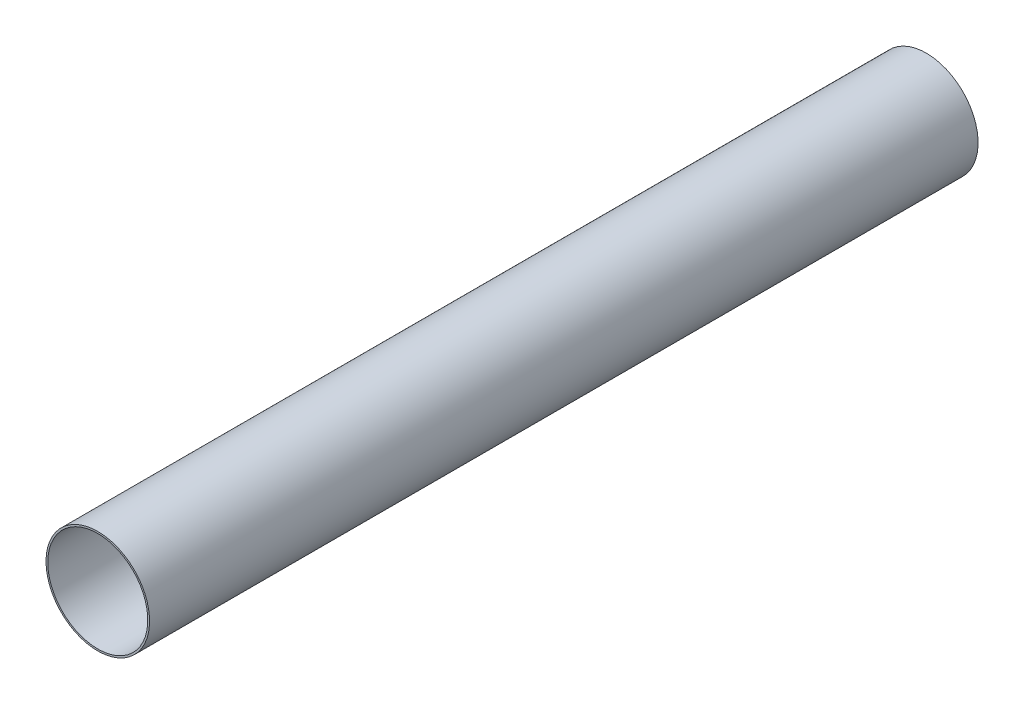
SolidWorks part; units mm, degrees
ref_plane "Plan de face" through (0, 0, 0) normal (0, 0, 1) x (1, 0, 0)
ref_plane "Plan de dessus" through (0, 0, 0) normal (0, 1, 0) x (1, 0, 0)
ref_plane "Plan de droite" through (0, 0, 0) normal (1, 0, 0) x (0, 0, -1)
sketch "Esquisse1" plane through (0, 0, 0) normal (0, 0, 1) x (1, 0, 0)
  circle A0 centre (0, 0) radius 76.2 construction
  circle A1 centre (0, 0) radius 73.6092 construction
  circle A2 centre (0, 0) radius 76.2
  circle A3 centre (0, 0) radius 73.6092
extrude "Boss.-Extru.1" add sketch "Esquisse1" along normal blind 1219.2 contours A2 | A3
